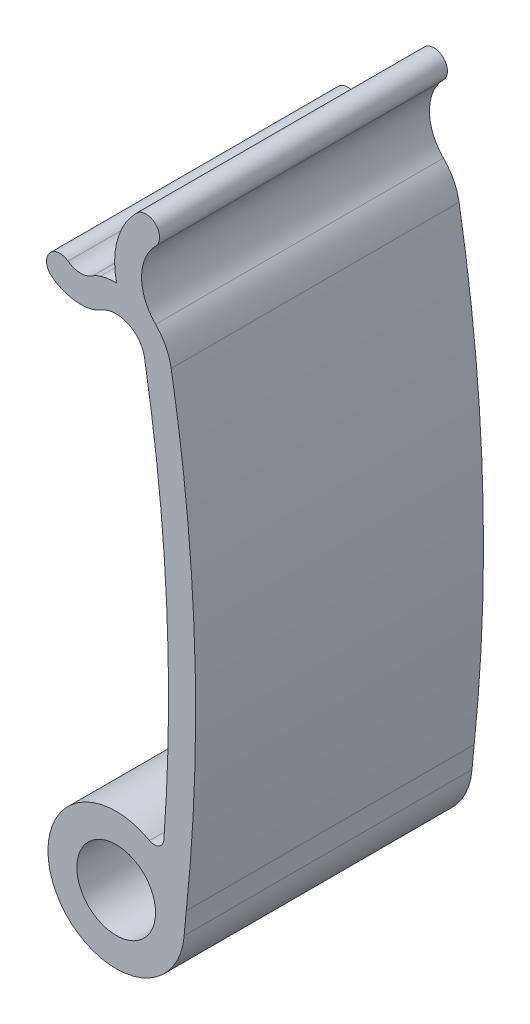
SolidWorks part; units mm, degrees
ref_plane "Front Plane" through (0, 0, 0) normal (0, 0, 1) x (1, 0, 0)
ref_plane "Top Plane" through (0, 0, 0) normal (0, 1, 0) x (1, 0, 0)
ref_plane "Right Plane" through (0, 0, 0) normal (1, 0, 0) x (0, 0, -1)
sketch "Sketch1" plane through (0, 0, 0) normal (0, 0, 1) x (1, 0, 0)
  circle A0 centre (0, 0) radius 4.1
  arc A18 (2.1213, 62.1522) -> (0.0537, 54.8098) centre (7.6368, 56.6368) ccw
  arc A24 (4.1083, 60.1652) -> (2.1213, 62.1522) centre (3.1148, 61.1587) ccw
  arc A29 (-5.0083, 54.248) -> (-6.6943, 52) centre (-5.8513, 53.124) ccw
  arc A31 (0.0537, 54.8098) -> (-1.6444, 54.5724) centre (0, 49) ccw
  arc A32 (-5.0083, 54.248) -> (-2.471, 54.1835) centre (-3.6943, 56) ccw
  arc A33 (-2.471, 54.1835) -> (-1.6444, 54.5724) centre (-0.7953, 51.6951) cw
  arc A34 (-6.6943, 52) -> (-3.2118, 51.0233) centre (-3.6943, 56) ccw
  arc A36 (-3.2118, 51.0233) -> (-1.5419, 51.5734) centre (-3.5978, 55.0047) ccw
  arc A37 (2.9634, 49.4669) -> (-1.5419, 51.5734) centre (0, 49) ccw
  arc A38 (4.1083, 60.1652) -> (4.1083, 53.1083) centre (7.6368, 56.6368) ccw
  arc A39 (3.4817, 6.1992) -> (7.0864, -0.5787) centre (0, 0) ccw
  arc A42 (5.7333, 49.9408) -> (4.1083, 53.1083) centre (0, 49) ccw
  arc A43 (4.9685, 6.9961) -> (2.9634, 49.4669) centre (-168.8273, 20.0737) ccw
  arc A44 (7.3075, 1.7829) -> (5.7333, 49.9408) centre (-167.0149, 20.1894) ccw
  arc A45 (3.4817, 6.1992) -> (4.9685, 6.9961) centre (3.9714, 7.0711) ccw
  arc A46 (7.0864, -0.5787) -> (7.3075, 1.7829) centre (106.7546, -8.7177) cw
  point P30 (0, 0)
extrude "Boss-Extrude1" add sketch "Sketch1" along normal blind 30
